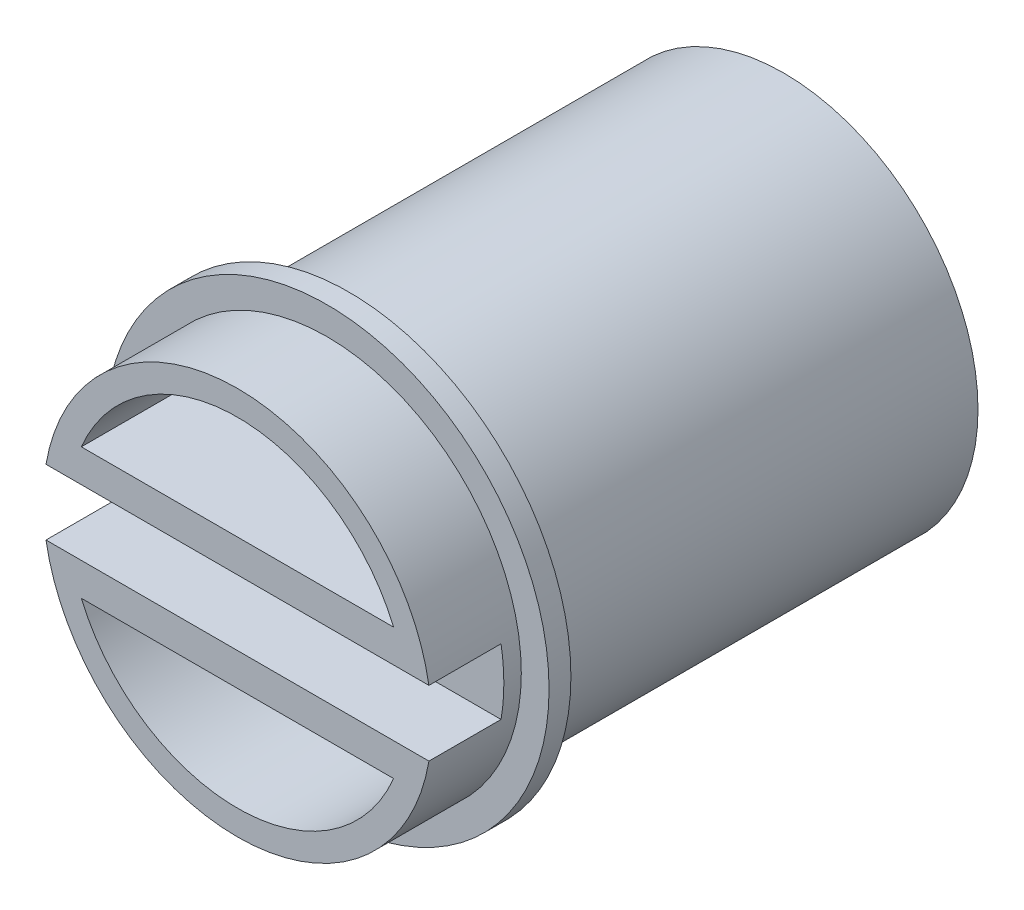
SolidWorks part; units mm, degrees
ref_plane "Front Plane" through (0, 0, 0) normal (0, 0, 1) x (1, 0, 0)
ref_plane "Top Plane" through (0, 0, 0) normal (0, 1, 0) x (1, 0, 0)
ref_plane "Right Plane" through (0, 0, 0) normal (1, 0, 0) x (0, 0, -1)
sketch "Sketch1" plane through (0, 0, 0) normal (0, 0, 1) x (1, 0, 0)
  circle A1 centre (0, 0) radius 101.6
  dimension "D3" = 203.2
extrude "Boss-Extrude1" add sketch "Sketch1" against normal blind 250
sketch "Sketch2" plane through (0, 0, 0) normal (0, 0, 1) x (1, 0, 0)
  line L0 (-87.6254, 15) -> (87.6254, 15)
  line L2 (87.6254, -15) -> (-87.6254, -15)
  circle A0 centre (0, 0) radius 88.9
  dimension "D1" = 177.8
  dimension "D2" = 30
extrude "Cut-Extrude1" cut sketch "Sketch2" against normal blind 33 contours L0 A0 L2
sketch "Sketch4" plane through (0, 0, 0) normal (0, 0, 1) x (1, 0, 0)
  circle A0 centre (0, 0) radius 101.6
  circle A1 centre (0, 0) radius 88.9
  dimension "D1" = 177.8
extrude "Cut-Extrude2" cut sketch "Sketch4" against normal blind 41
sketch "Sketch5" plane through (0, 0, -250) normal (0, 0, -1) x (-1, 0, 0)
  circle A0 centre (0, 0) radius 88.9
  circle A1 centre (0, 0) radius 101.6
  dimension "D1" = 177.8
extrude "Cut-Extrude3" cut sketch "Sketch5" against normal blind 199
sketch "Sketch6" plane through (0, 0, 0) normal (0, 0, 1) x (1, 0, 0)
  line L0 (-71.458, 30) -> (71.458, 30)
  line L1 (-71.458, -30) -> (71.458, -30)
  line L2 (-87.6254, 15) -> (87.6254, 15) construction
  line L3 (87.6254, -15) -> (-87.6254, -15) construction
  line L4 (-25, 15) -> (25, 15)
  line L5 (-87.6254, 15) -> (87.6254, 15) construction
  line L6 (25, 15) -> (25, -15)
  line L7 (87.6254, -15) -> (-87.6254, -15) construction
  line L8 (25, -15) -> (-25, -15)
  line L9 (-25, -15) -> (-25, 15)
  arc A0 (-71.458, -30) -> (71.458, -30) centre (0, 0) ccw
  arc A1 (71.458, 30) -> (-71.458, 30) centre (0, 0) ccw
  dimension "D3" = 155
  dimension "D1" = 15
  dimension "D2" = 15
  dimension "D4" = 25
  dimension "D5" = 25
extrude "Cut-Extrude4" cut sketch "Sketch6" against normal blind 287
